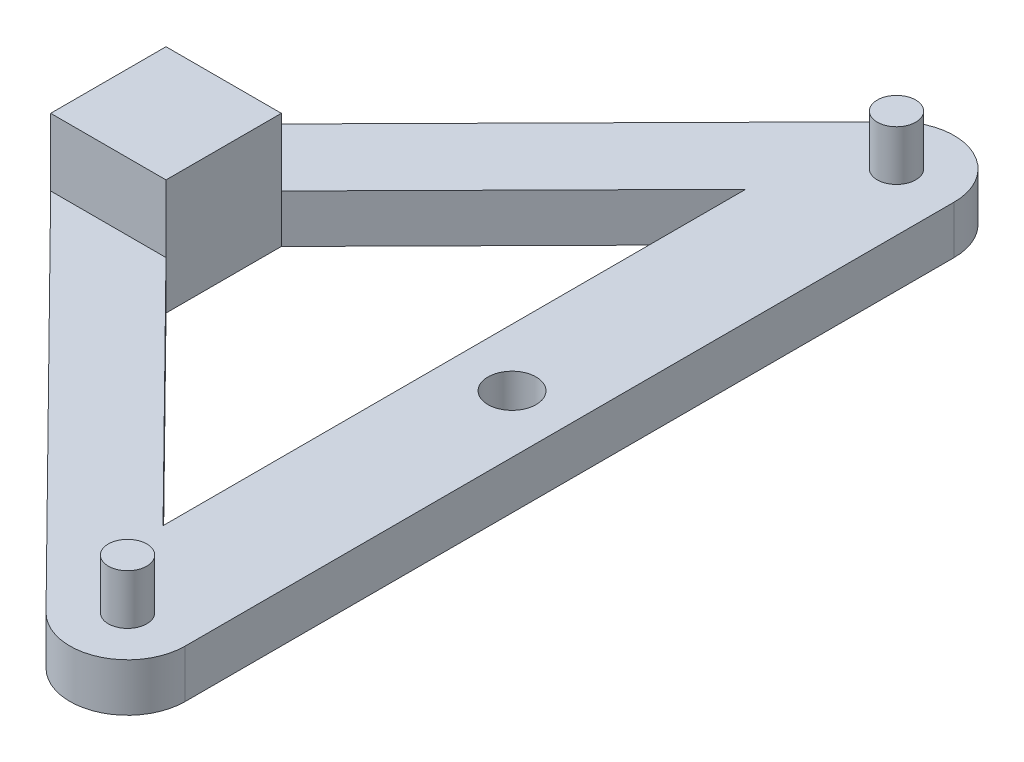
SolidWorks part; units mm, degrees
ref_plane "Front Plane" through (0, 0, 0) normal (0, 0, 1) x (1, 0, 0)
ref_plane "Top Plane" through (0, 0, 0) normal (0, 1, 0) x (1, 0, 0)
ref_plane "Right Plane" through (0, 0, 0) normal (1, 0, 0) x (0, 0, -1)
sketch "Sketch1" plane through (0, 0, 0) normal (0, 1, 0) x (1, 0, 0)
  line L1 (-3.81, 19.2459) -> (-3.81, -19.2459)
  line L2 (3.81, 25.4) -> (3.81, -25.4)
  line L4 (-26.67, 3.81) -> (-2.7112, 28.0768)
  line L5 (-26.67, -3.81) -> (-19.05, -3.81)
  line L6 (-26.67, -3.81) -> (-26.67, 3.81)
  line L7 (-26.67, 3.81) -> (-19.05, 3.81)
  line L8 (-19.05, -3.81) -> (-19.05, 3.81)
  line L9 (-26.67, -3.81) -> (-19.05, 3.81) construction
  line L10 (-26.67, 3.81) -> (-19.05, -3.81) construction
  line L11 (-19.05, 3.81) -> (-3.81, 19.2459)
  line L12 (-26.67, -3.81) -> (-2.7112, -28.0768)
  line L13 (-19.05, -3.81) -> (-3.81, -19.2459)
  arc A1 (-2.7112, -28.0768) -> (3.81, -25.4) centre (0, -25.4) ccw
  arc A2 (3.81, 25.4) -> (-2.7112, 28.0768) centre (0, 25.4) ccw
  point P0 (-2.6141, 40.9264)
  point P4 (0, 0)
  dimension "D1" = 0
  dimension "D6" = 180
  dimension "D7" = 3.81
  dimension "D9" = 25.4
  dimension "D11" = 3.81
  dimension "D2" = 180
  dimension "D3" = 3.81
  dimension "D4" = 7.62
  dimension "D5" = 7.62
  dimension "D8" = 7.62
  dimension "D10" = 25.4
  dimension "D12" = 19.05
sketch "Sketch10" plane through (0, 0, 0) normal (0, 1, 0) x (1, 0, 0)
  line L0 (-3.81, 19.2459) -> (-3.81, -19.2459)
  line L1 (3.81, 25.4) -> (3.81, -25.4)
  line L2 (-26.67, 3.81) -> (-2.7112, 28.0768)
  line L3 (-26.67, -3.81) -> (-19.05, -3.81)
  line L4 (-26.67, 3.81) -> (-19.05, 3.81)
  line L5 (-19.05, 3.81) -> (-3.81, 19.2459)
  line L6 (-26.67, -3.81) -> (-2.7112, -28.0768)
  line L7 (-19.05, -3.81) -> (-3.81, -19.2459)
  arc A0 (-2.7112, -28.0768) -> (3.81, -25.4) centre (0, -25.4) ccw
  arc A1 (3.81, 25.4) -> (-2.7112, 28.0768) centre (0, 25.4) ccw
extrude "Boss-Extrude4" add sketch "Sketch10" along normal blind 3.175
sketch "Sketch11" plane through (0, 0, 0) normal (0, 1, 0) x (1, 0, 0)
  line L0 (-26.67, -3.81) -> (-19.05, -3.81)
  line L1 (-26.67, -3.81) -> (-26.67, 3.81)
  line L2 (-26.67, 3.81) -> (-19.05, 3.81)
  line L3 (-19.05, -3.81) -> (-19.05, 3.81)
extrude "Boss-Extrude5" add sketch "Sketch11" along normal blind 7.62
sketch "Sketch12" plane through (0, 3.175, 0) normal (0, 1, 0) x (1, 0, 0)
  circle A0 centre (0, 0) radius 1.5875
  circle A1 centre (0, -25.4) radius 1.27
  circle A2 centre (0, 25.4) radius 1.27
  dimension "D1" = 2.54
  dimension "D2" = 3.175
  dimension "D3" = 2.54
sketch "Sketch13" plane through (0, 3.175, 0) normal (0, 1, 0) x (1, 0, 0)
  circle A0 centre (0, -25.4) radius 1.27
  circle A1 centre (0, 25.4) radius 1.27
extrude "Boss-Extrude6" add sketch "Sketch13" along normal blind 3.302
sketch "Sketch14" plane through (0, 3.175, 0) normal (0, 1, 0) x (1, 0, 0)
  circle A0 centre (0, 0) radius 1.5875
extrude "Cut-Extrude3" cut sketch "Sketch14" against normal up to surface (3.175 mm away) up to plane "Top Plane"
sketch "Sketch15" plane through (-26.67, 0, 0) normal (-1, 0, 0) x (0, 0, 1)
  line L0 (0, 7.62) -> (0, 0) construction
  line L1 (-3.81, 7.62) -> (3.81, 7.62) construction
  line L2 (-3.81, 7.62) -> (-3.81, 0)
  line L3 (-3.81, 0) -> (-19.2459, 0) construction
  line L4 (-3.81, 3.175) -> (-3.81, 0) construction
  line L5 (3.81, 7.62) -> (3.81, 0)
  line L6 (3.81, 0) -> (19.2459, 0) construction
  line L7 (-25.4, 0) -> (25.4, 0) construction
  line L8 (-3.81, 3.81) -> (3.81, 3.81)
  circle A0 centre (0, 3.81) radius 1.651
sketch "Sketch16" plane through (-26.67, 0, 0) normal (-1, 0, 0) x (0, 0, 1)
  circle A0 centre (0, 3.81) radius 1.651
extrude "Cut-Extrude4" cut sketch "Sketch16" against normal blind 3.81
